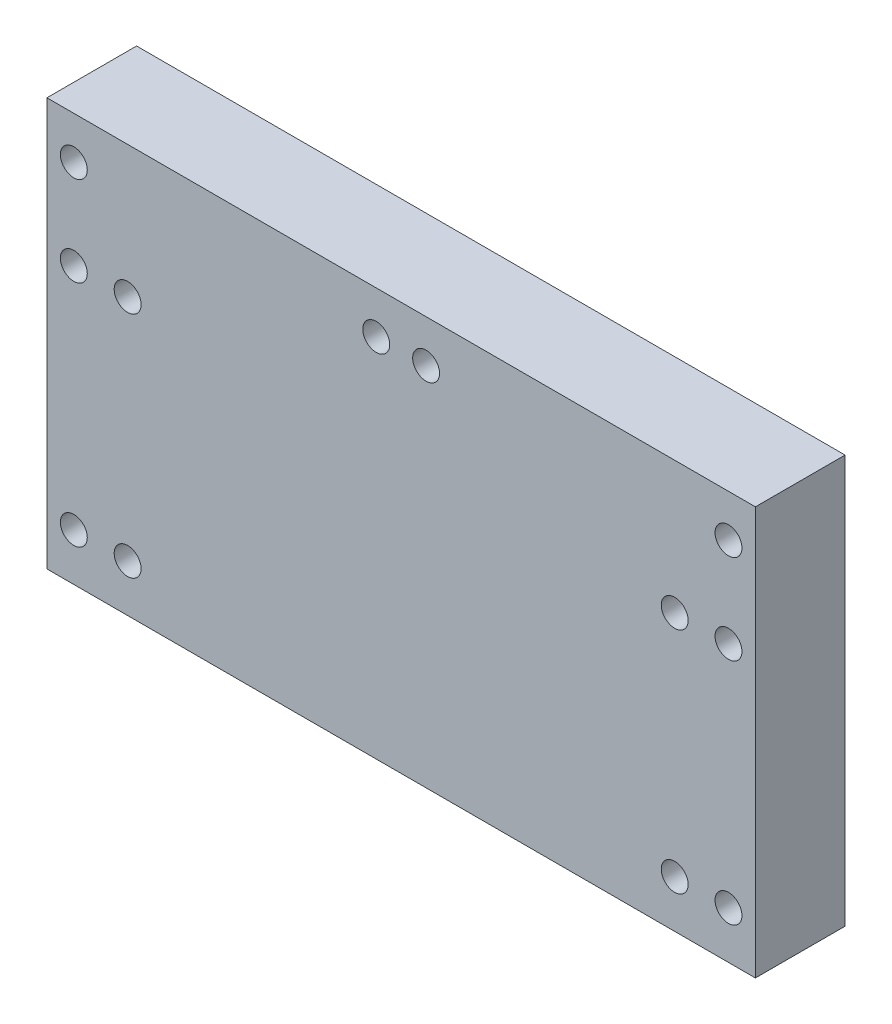
SolidWorks part; units mm, degrees
ref_plane "前视基准面" through (0, 0, 0) normal (0, 0, 1) x (1, 0, 0)
ref_plane "上视基准面" through (0, 0, 0) normal (0, 1, 0) x (1, 0, 0)
ref_plane "右视基准面" through (0, 0, 0) normal (1, 0, 0) x (0, 0, -1)
sketch "草图1" plane through (0, 0, 0) normal (0, 0, 1) x (1, 0, 0)
  line L0 (-39.5, 22.75) -> (-39.5, 9.98)
  line L1 (-39.5, 22.75) -> (39.5, 22.75)
  line L2 (-39.5, 22.75) -> (-39.5, -22.75)
  line L3 (-39.5, -22.75) -> (39.5, -22.75)
  line L4 (39.5, 22.75) -> (39.5, -22.75)
  line L5 (-39.5, 22.75) -> (39.5, -22.75) construction
  line L6 (-39.5, -22.75) -> (39.5, 22.75) construction
  line L7 (-30.5, 8.02) -> (-36.5, 8.02)
  line L8 (-30.5, -17.48) -> (-36.5, -17.48)
  line L9 (-39.5, 22.75) -> (-33.5, 22.75)
  line L12 (0, 22.75) -> (0, -28.661) construction
  line L13 (0, 22.75) -> (0, 16.75)
  line L14 (6, 16.75) -> (-6, 16.75)
  line L15 (-6, 16.75) -> (-6, 22.75)
  line L16 (6, 16.75) -> (6, 22.75)
  line L19 (-39.5, -22.75) -> (-33.5, -22.75)
  line L21 (-33.5, 8.02) -> (-33.5, -17.48)
  line L22 (36.5, 18.02) -> (36.5, 8.02) construction
  line L24 (-36.5, 18.02) -> (36.5, 18.02) construction
  circle A0 centre (-36.5, 18.02) radius 1.5
  circle A2 centre (-2.7807, 18.02) radius 1.5
  circle A3 centre (2.7807, 18.02) radius 1.5
  circle A4 centre (36.5, 18.02) radius 1.5
  circle A6 centre (-36.5, 8.02) radius 1.5
  circle A7 centre (-36.5, -17.48) radius 1.5
  circle A8 centre (-30.5, 8.02) radius 1.5
  circle A9 centre (-30.5, -17.48) radius 1.5
  circle A10 centre (30.5, -17.48) radius 1.5
  circle A11 centre (36.5, -17.48) radius 1.5
  circle A12 centre (30.5, 8.02) radius 1.5
  circle A13 centre (36.5, 8.02) radius 1.5
  point P0 (0, 0)
  point P35 (-33.5, -4.73)
  point P36 (-33.5, 8.02)
  point P39 (-33.5, -17.48)
  dimension "D3" = 5.27
  dimension "D5" = 10
  dimension "D1" = 79
  dimension "D2" = 45.5
  dimension "D4" = 25.5
extrude "凸台-拉伸1" add sketch "草图1" along normal blind 10
